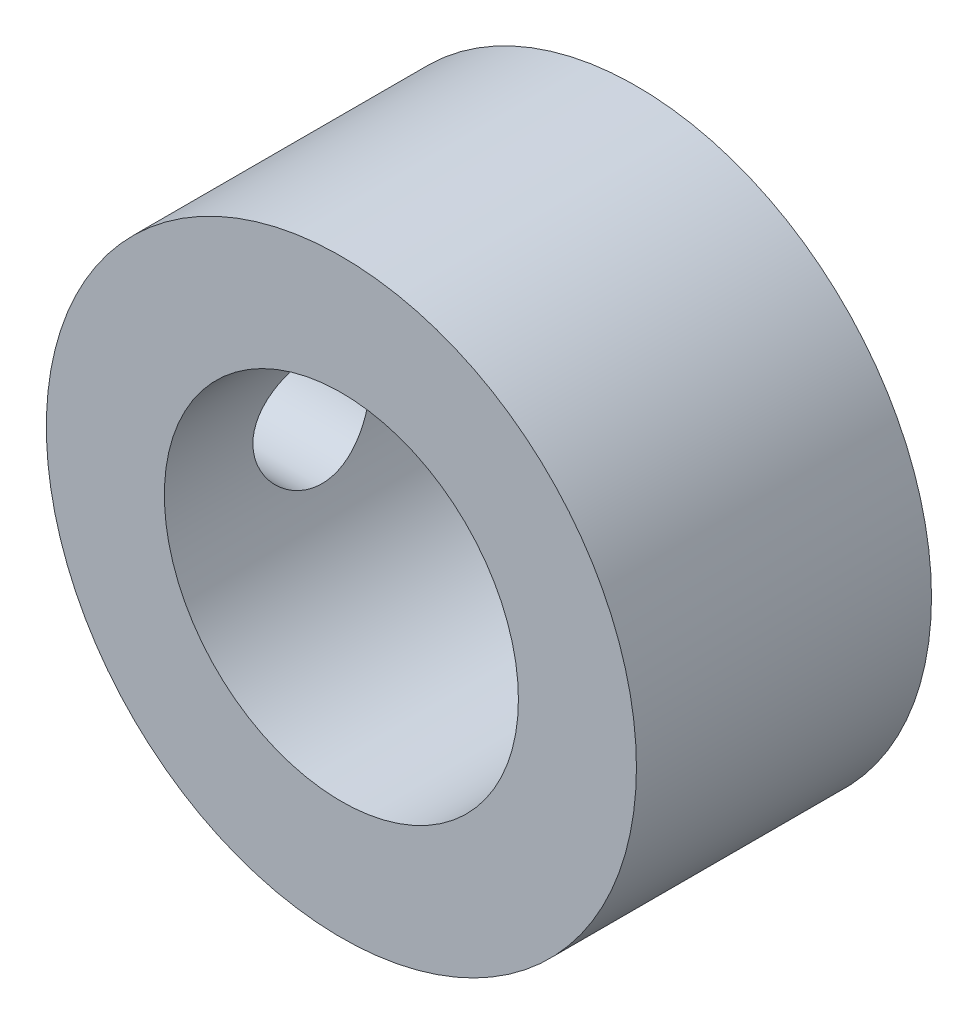
SolidWorks part; units mm, degrees
material "3.3547 (EN-AW 5083)"
ref_plane "Ebene vorne" through (0, 0, 0) normal (0, 0, 1) x (1, 0, 0)
ref_plane "Ebene oben" through (0, 0, 0) normal (0, 1, 0) x (1, 0, 0)
ref_plane "Ebene rechts" through (0, 0, 0) normal (1, 0, 0) x (0, 0, -1)
sketch "Skizze1" plane through (0, 0, 0) normal (0, 0, 1) x (1, 0, 0)
  circle A0 centre (0, 0) radius 10
  circle A1 centre (0, 0) radius 6
extrude "Aufsatz-Linear austragen1" add sketch "Skizze1" along normal blind 10
sketch "Skizze2" plane through (0, 0, 0) normal (1, 0, 0) x (0, 0, -1)
  line L0 (-10, 10) -> (-10, -10) construction
  circle A0 centre (-5, 0) radius 2
  dimension "D1" = 5
extrude "Schnitt-Linear austragen1" cut sketch "Skizze2" against normal blind 18
